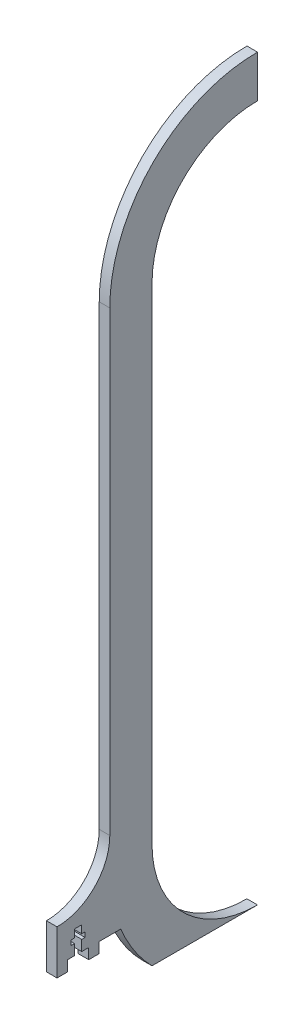
SolidWorks part; units mm, degrees
ref_plane "Front Plane" through (0, 0, 0) normal (0, 0, 1) x (1, 0, 0)
ref_plane "Top Plane" through (0, 0, 0) normal (0, 1, 0) x (1, 0, 0)
ref_plane "Right Plane" through (0, 0, 0) normal (1, 0, 0) x (0, 0, -1)
sketch "Elevator Ball Support Rail" plane through (0, 0, 0) normal (1, 0, 0) x (0, 0, -1)
  line L0 (63.5, 209.55) -> (63.5, 234.95)
  line L2 (63.5, -209.55) -> (0, -209.55)
  line L3 (-31.75, -180.975) -> (-18.7887, -180.975)
  line L4 (-38.1, -187.325) -> (-31.75, -187.325)
  line L5 (-38.1, -180.975) -> (-38.1, -187.325)
  line L6 (0, 146.05) -> (0, -146.05)
  line L7 (-25.4, -128.905) -> (-25.4, -180.975) construction
  line L8 (0, -146.05) -> (0, -209.55) construction
  line L9 (-31.75, -180.975) -> (-31.75, -187.325)
  line L10 (-50.8, -180.975) -> (-46.609, -180.975)
  line L11 (-25.4, 146.05) -> (-25.4, -128.905)
  line L12 (-57.15, -160.655) -> (-57.15, -187.325)
  line L13 (-57.15, -187.325) -> (-50.8, -187.325)
  line L14 (-42.291, -180.975) -> (-38.1, -180.975)
  line L15 (-50.8, -187.325) -> (-50.8, -180.975)
  line L16 (-42.291, -174.625) -> (-42.291, -180.975)
  line L17 (-42.291, -174.625) -> (-40.25, -174.625)
  line L18 (-40.25, -174.625) -> (-40.25, -171.725)
  line L19 (-42.291, -171.725) -> (-42.291, -167.005)
  line L20 (-42.291, -167.005) -> (-46.609, -167.005)
  line L21 (-40.25, -171.725) -> (-42.291, -171.725)
  line L22 (-48.65, -171.725) -> (-48.65, -174.625)
  line L23 (-48.65, -174.625) -> (-46.609, -174.625)
  line L24 (-46.609, -174.625) -> (-46.609, -180.975)
  line L25 (-46.609, -167.005) -> (-46.609, -171.725)
  line L26 (-46.609, -171.725) -> (-48.65, -171.725)
  line L27 (0, -180.975) -> (101.6, -180.975) construction
  arc A0 (0, 146.05) -> (63.5, 209.55) centre (63.5, 146.05) cw
  arc A1 (63.5, 234.95) -> (-25.4, 146.05) centre (63.5, 146.05) ccw
  arc A2 (0, -146.05) -> (63.5, -209.55) centre (63.5, -146.05) ccw
  arc A3 (-18.7887, -180.975) -> (0, -209.55) centre (63.5, -147.333) ccw
  arc A4 (-57.15, -160.655) -> (-25.4, -128.905) centre (-57.15, -128.905) ccw
  point P4 (0, 0)
  dimension "D5" = 25.4
  dimension "D4" = 63.5
  dimension "D7" = 63.5
  dimension "D8" = 6.35
  dimension "D14" = 12.7
  dimension "D13" = 6.35
  dimension "D6" = 6.35
  dimension "D1" = 25.4
  dimension "D3" = 292.1
  dimension "D9" = 22.225
  dimension "D10" = 6.35
  dimension "D11" = 6.35
  dimension "D12" = 6.35
  dimension "D15" = 2.9
  dimension "D16" = 8.4
  dimension "D17" = 6.35
  dimension "D18" = 4.318
  dimension "D19" = 13.97
  dimension "D20" = 34.925
extrude "Boss-Extrude2" add sketch "Elevator Ball Support Rail" along normal blind 6.35 contours L5 L4 L9 L3 A3 L2 A2 L6 A0 L0 A1 L11 A4 L12 L13 L15 L10 L24 L23 L22 L26 L25 L20 L19 L21 L18 L17 L16 L14
equation "\"Ball Diameter\"= 1.75in"
equation "\"Pulley Diameter\" = 1in"
equation "\"Reactor Height\" = 14in"
equation "\"Sheet Thickness\"= 0.25in"
equation "\"Screw Diameter\"= .17in"
equation "\"Robot Diameter\"= 14in"
equation "\"Castor Screw Diameter\"= 0.22in"
equation "\"Wheel Diameter\" = 4in"
equation "\"Nut Diameter\" = 8.4mm"
equation "\"Nut Height\" = 2.9mm"
equation "\"Screw Height\" = 0.55in"
equation "\"D11@Elevator Ball Support Rail\"=\"Sheet Thickness\""
equation "\"Elevator Height\" = 11.5in"
equation "\"D12@Elevator Ball Support Rail\"=\"Sheet Thickness\""
equation "\"D7@Elevator Ball Support Rail\"=(\"Pulley Diameter\"/2) + \"Ball Diameter\" + 0.25in"
equation "\"D10@Elevator Ball Support Rail\"=\"Sheet Thickness\""
equation "\"D13@Elevator Ball Support Rail\"=\"Sheet Thickness\""
equation "\"D1@T-Slot\" = \"Screw Diameter\""
equation "\"D16@Elevator Ball Support Rail\"=\"Nut Diameter\""
equation "\"D15@Elevator Ball Support Rail\"=\"Nut Height\""
equation "\"D16@Elevator Ball Support Rail\" = \"Nut Diameter\""
equation "\"D9@Elevator Ball Support Rail\"=\"Ball Diameter\"/2"
equation "\"D1@Boss-Extrude2\"=\"Sheet Thickness\""
equation "\"D18@Elevator Ball Support Rail\"=\"Screw Diameter\""
equation "\"D19@Elevator Ball Support Rail\"=\"Screw Height\""
equation "\"D3@Elevator Ball Support Rail\"=\"Elevator Height\""
